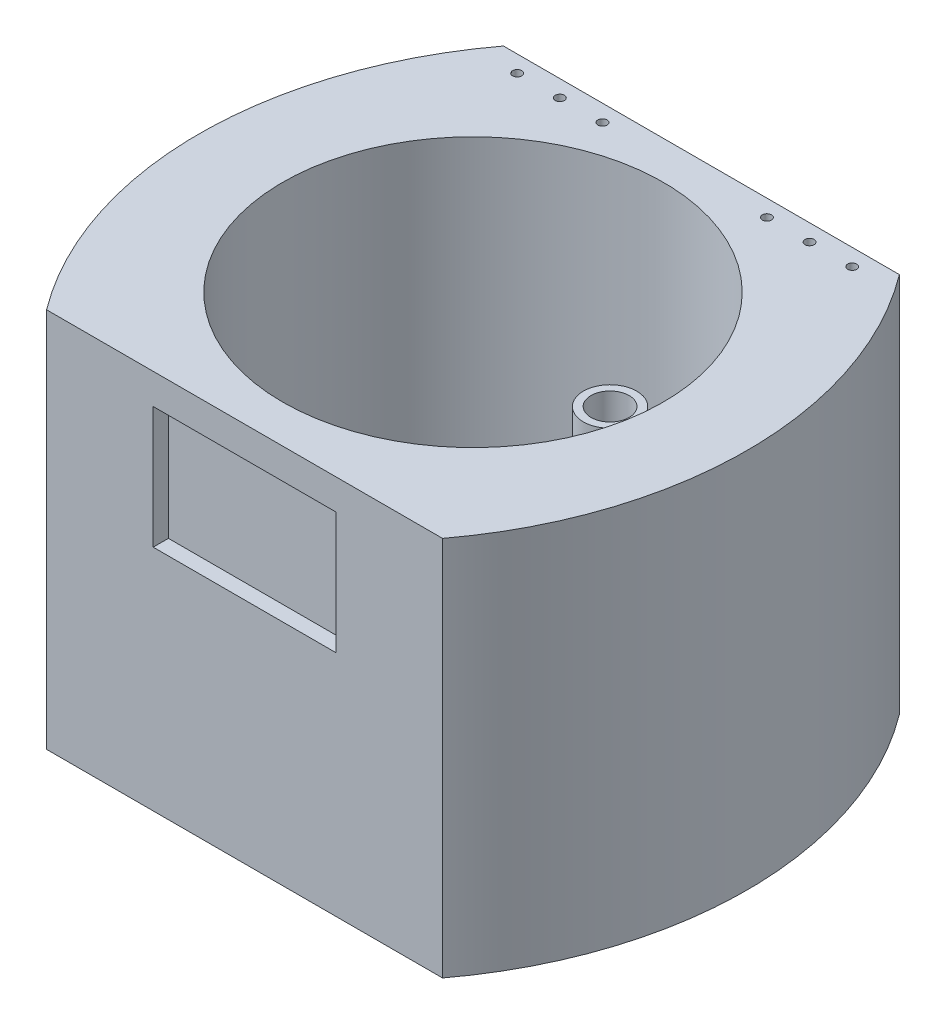
SolidWorks part; units mm, degrees
ref_plane "Front Plane" through (0, 0, 0) normal (0, 0, 1) x (1, 0, 0)
ref_plane "Top Plane" through (0, 0, 0) normal (0, 1, 0) x (1, 0, 0)
ref_plane "Right Plane" through (0, 0, 0) normal (1, 0, 0) x (0, 0, -1)
sketch "Case" plane through (0, 0, 0) normal (0, 1, 0) x (1, 0, 0)
  line L0 (-130, 150) -> (130, 150)
  line L1 (-130, -150) -> (130, -150)
  arc A4 (-130, 150) -> (-130, -150) centre (70, 0) ccw
  arc A5 (130, 150) -> (130, -150) centre (-70, 0) cw
  dimension "D1" = 130
  dimension "D6" = 250
  dimension "D7" = 250
  dimension "D2" = 260
  dimension "D3" = 130
  dimension "D4" = 150
  dimension "D5" = 150
extrude "Boss-Extrude1" add sketch "Case" along normal blind 250
sketch "Inside Compartment" plane through (0, 250, 0) normal (0, 1, 0) x (1, 0, 0)
  circle A0 centre (0, 0) radius 125
  dimension "D1" = 250
extrude "Cut-Extrude1" cut sketch "Inside Compartment" against normal blind 240
sketch "LCD" plane through (0, 0, 150) normal (0, 0, 1) x (1, 0, 0)
  line L0 (130, 250) -> (130, 0) construction
  line L1 (-60, 230) -> (60, 230)
  line L2 (-60, 230) -> (-60, 150)
  line L3 (-60, 150) -> (60, 150)
  line L4 (60, 230) -> (60, 150)
  line L6 (-130, 0) -> (130, 0) construction
  dimension "D1" = 120
  dimension "D2" = 80
  dimension "D3" = 70
  dimension "D4" = 150
extrude "Cut-Extrude2" cut sketch "LCD" against normal blind 10
sketch "Hinge holes" plane through (0, 250, 0) normal (0, 1, 0) x (1, 0, 0)
  line L0 (130, 150) -> (-130, 150) construction
  circle A0 centre (-110, 139) radius 3
  circle A1 centre (-82, 139) radius 3
  circle A2 centre (-54, 139) radius 3
  circle A3 centre (54, 139) radius 3
  circle A4 centre (82, 139) radius 3
  circle A5 centre (110, 139) radius 3
  dimension "D1" = 6
  dimension "D2" = 28
  dimension "D3" = 28
  dimension "D4" = 28
  dimension "D5" = 28
  dimension "D6" = 11
  dimension "D7" = 20
  dimension "D8" = 20
extrude "Cut-Extrude3" cut sketch "Hinge holes" against normal blind 20
sketch "Power supply holes" plane through (0, 10, 0) normal (0, 1, 0) x (1, 0, 0)
  line L0 (130, 150) -> (-130, 150) construction
  circle A0 centre (-82.5, 40) radius 3.5
  circle A1 centre (37.5, 40) radius 3.5
  circle A2 centre (37.5, -40) radius 3.5
  circle A3 centre (-82.5, -40) radius 3.5
  dimension "D1" = 7
  dimension "D2" = 80
  dimension "D3" = 120
  dimension "D4" = 110
  dimension "D5" = 82.5
extrude "Cut-Extrude4" cut sketch "Power supply holes" against normal through all
sketch "Poles for middle layer" plane through (0, 10, 0) normal (0, 1, 0) x (1, 0, 0)
  circle A0 centre (0, 90) radius 17.5
  circle A1 centre (0, -90) radius 17.5
  dimension "D1" = 35
  dimension "D2" = 90
  dimension "D3" = 90
extrude "Boss-Extrude2" add sketch "Poles for middle layer" along normal blind 130
sketch "Holes for poles" plane through (0, 140, 0) normal (0, 1, 0) x (1, 0, 0)
  circle A0 centre (0, -90) radius 12.5
  circle A1 centre (0, 90) radius 12.5
  dimension "D1" = 25
extrude "Cut-Extrude6" cut sketch "Holes for poles" against normal blind 50
